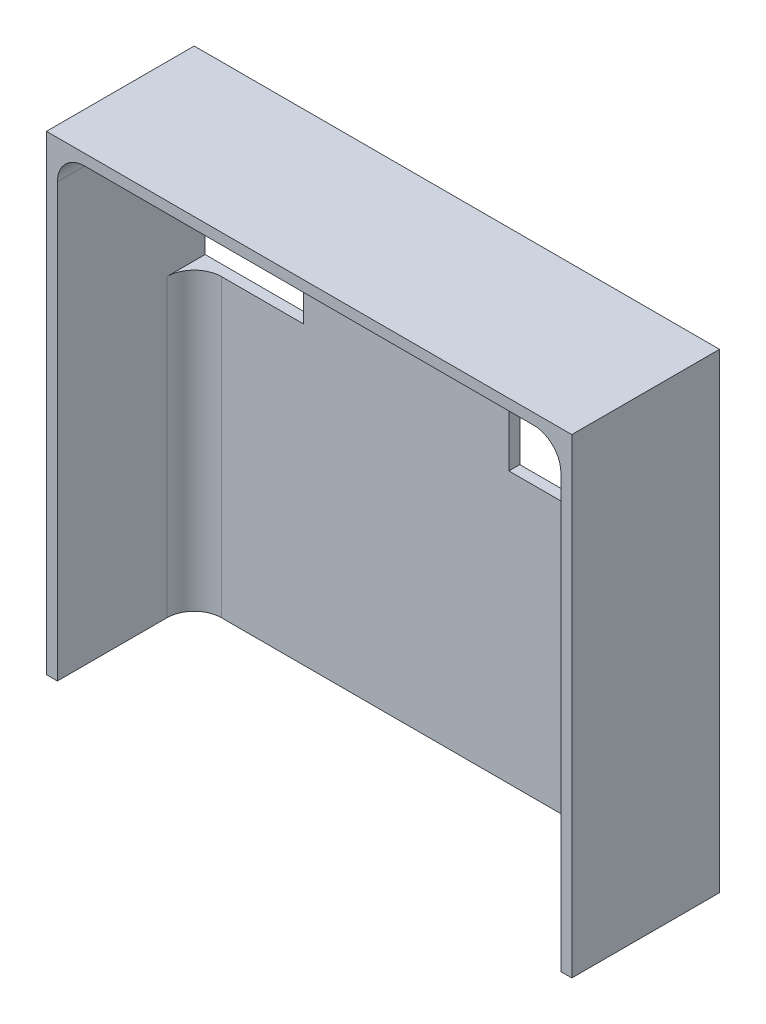
SolidWorks part; units mm, degrees
ref_plane "Front Plane" through (0, 0, 0) normal (0, 0, 1) x (1, 0, 0)
ref_plane "Top Plane" through (0, 0, 0) normal (0, 1, 0) x (1, 0, 0)
ref_plane "Right Plane" through (0, 0, 0) normal (1, 0, 0) x (0, 0, -1)
sketch "Sketch1" plane through (0, 0, 0) normal (0, 0, 1) x (1, 0, 0)
  line L1 (-392.5, 172.5) -> (-296.5, 172.5)
  line L2 (-392.5, 172.5) -> (-392.5, 86.5)
  line L3 (-392.5, 86.5) -> (-296.5, 86.5)
  line L4 (-296.5, 172.5) -> (-296.5, 86.5)
  dimension "D1" = 96
  dimension "D2" = 86
extrude "Boss-Extrude1" add sketch "Sketch1" along normal blind 2
sketch "Sketch2" plane through (0, 0, 2) normal (0, 0, 1) x (1, 0, 0)
  line L0 (-296.5, 86.5) -> (-296.5, 172.5) construction
  line L1 (-296.5, 172.5) -> (-298.5, 172.5)
  line L2 (-296.5, 172.5) -> (-296.5, 86.5)
  line L3 (-296.5, 86.5) -> (-298.5, 86.5)
  line L4 (-298.5, 170.5) -> (-298.5, 86.5)
  line L5 (-392.5, 86.5) -> (-296.5, 86.5) construction
  line L7 (-392.5, 172.5) -> (-390.5, 172.5)
  line L8 (-392.5, 172.5) -> (-392.5, 86.5)
  line L9 (-392.5, 86.5) -> (-390.5, 86.5)
  line L10 (-390.5, 170.5) -> (-390.5, 86.5)
  line L11 (-296.5, 172.5) -> (-392.5, 172.5)
  line L12 (-296.5, 172.5) -> (-296.5, 170.5)
  line L13 (-298.5, 170.5) -> (-390.5, 170.5)
  line L14 (-392.5, 172.5) -> (-392.5, 170.5)
  line M5 (-392.5, 172.5) -> (-392.5, 86.5)
  line M6 (-392.5, 86.5) -> (-296.5, 86.5)
  line M7 (-296.5, 86.5) -> (-296.5, 172.5)
  line M8 (-296.5, 172.5) -> (-392.5, 172.5)
  dimension "D1" = 2
  dimension "D2" = 2
  dimension "D3" = 2
extrude "Boss-Extrude3" add sketch "Sketch2" along normal blind 25 contours L13 L4 L2 L8 L10 M6 M7 M8 M5
sketch "Sketch3" plane through (0, 0, 0) normal (0, 0, -1) x (-1, 0, 0)
  line L0 (296.5, 172.5) -> (392.5, 172.5) construction
  line L1 (390.5, 170.5) -> (370.5, 170.5)
  line L2 (390.5, 170.5) -> (390.5, 140.5)
  line L3 (390.5, 140.5) -> (370.5, 140.5)
  line L4 (370.5, 170.5) -> (370.5, 140.5)
  line L5 (392.5, 172.5) -> (392.5, 86.5) construction
  dimension "D1" = 30
  dimension "D2" = 20
  dimension "D3" = 2
  dimension "D4" = 2
extrude "Cut-Extrude1" cut sketch "Sketch3" against normal blind 25
sketch "Sketch4" plane through (0, 0, 0) normal (0, 0, -1) x (-1, 0, 0)
  line L0 (296.5, 172.5) -> (392.5, 172.5) construction
  line L1 (318.5, 150.5) -> (333, 150.5)
  line L2 (318.5, 150.5) -> (318.5, 136)
  line L3 (318.5, 136) -> (333, 136)
  line L4 (333, 150.5) -> (333, 136)
  line L5 (296.5, 86.5) -> (296.5, 172.5) construction
  dimension "D1" = 22
  dimension "D2" = 22
  dimension "D3" = 14.5
extrude "Cut-Extrude2" cut sketch "Sketch4" against normal blind 25 contours L2 L1 L4 L3
sketch "Sketch5" plane through (0, 0, 0) normal (0, 0, -1) x (-1, 0, 0)
  line L0 (296.5, 86.5) -> (296.5, 172.5) construction
  line L1 (306.5, 117.5) -> (319.5, 117.5)
  line L2 (306.5, 117.5) -> (306.5, 104.5)
  line L3 (306.5, 104.5) -> (319.5, 104.5)
  line L4 (319.5, 117.5) -> (319.5, 104.5)
  line L5 (296.5, 172.5) -> (392.5, 172.5) construction
  dimension "D1" = 10
  dimension "D2" = 55
  dimension "D3" = 13
  dimension "D4" = 13
extrude "Cut-Extrude3" cut sketch "Sketch5" against normal blind 25 contours L2 L1 L4 L3
fillet "Fillet1" radius 5 5 edges at (-298.5, 170.5, 14.5) (-390.5, 170.5, 13.5) (-390.5, 113.5, 2) (-334.5, 170.5, 2) (-298.5, 128.5, 2)
